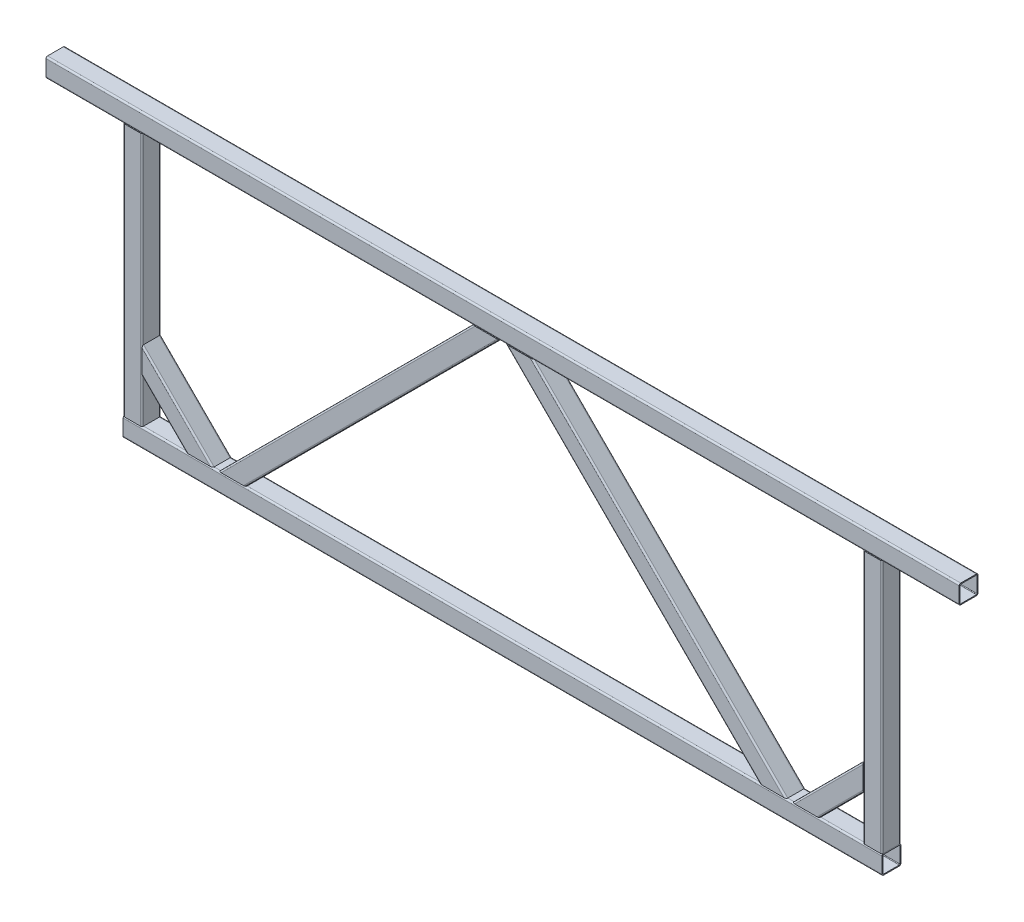
SolidWorks part; units mm, degrees
other "Вид с разнесенными частями1" [suppressed]
other "Шаг разнесения детали1" [suppressed]
other "Линия разнесения1"
other "Линия разнесения2"
other "Линия разнесения3"
other "Линия разнесения4"
other "Линия разнесения5"
other "Линия разнесения6"
other "Линия разнесения7"
other "Линия разнесения8"
other "Вид с разнесенными частями2" [suppressed]
other "3DРазнести1" [suppressed]
other "Шаг разнесения детали1" [suppressed]
other "Линия разнесения1"
ref_plane "Спереди" through (0, 0, 0) normal (0, 0, 1) x (1, 0, 0)
ref_plane "Сверху" through (0, 0, 0) normal (0, 1, 0) x (1, 0, 0)
ref_plane "Справа" through (0, 0, 0) normal (1, 0, 0) x (0, 0, -1)
sketch "Эскиз1" plane through (0, 0, 0) normal (0, 0, 1) x (1, 0, 0)
  line L0 (0, 511.5706) -> (0, -433) construction
  line L1 (-1175, 433) -> (1175, 433)
  line L2 (-1175, 433) -> (-1175, -433)
  line L3 (-1175, -433) -> (1175, -433)
  line L4 (1175, 433) -> (1175, -433)
  line L5 (-1175, 433) -> (1175, -433) construction
  line L6 (-1175, -433) -> (1175, 433) construction
  line L8 (-888.425, -433) -> (-22.425, 433)
  line L9 (-1175, -433) -> (-888.425, -433) construction
  line L10 (-888.425, -433) -> (-888.425, -84.7308) construction
  line L11 (-933.275, -433) -> (-1175, -191.275)
  line L12 (933.275, -433) -> (1175, -191.275)
  line L13 (888.425, -433) -> (22.425, 433)
  line L14 (-1450, 433) -> (1450, 433)
  point P0 (0, 0)
  dimension "D1" = 866
  dimension "D2" = 2350
  dimension "D3" = 22.425
  dimension "D4" = 44.85
  dimension "D5" = 45
  dimension "D6" = 90
  dimension "D7" = 2900
other "Прямоугольная труба 60 X 40 X 3.2(1)"
ref_plane "Плоскость1" through (-1450, 433, 0) normal (1, 0, 0) x (0, 1, 0)
sketch "Sketch1" plane through (-1450, 433, 0) normal (1, 0, 0) x (0, 1, 0)
  line L0 (-25, -27) -> (25, -27)
  line L1 (-27, -25) -> (-27, 25)
  line L2 (25, 27) -> (-25, 27)
  line L3 (27, 25) -> (27, -25)
  line L4 (-25, -30) -> (25, -30)
  line L5 (-30, -25) -> (-30, 25)
  line L6 (25, 30) -> (-25, 30)
  line L7 (30, 25) -> (30, -25)
  arc A0 (30, 25) -> (25, 30) centre (25, 25) ccw
  arc A1 (25, -30) -> (30, -25) centre (25, -25) ccw
  arc A2 (-30, -25) -> (-25, -30) centre (-25, -25) ccw
  arc A3 (-25, 30) -> (-30, 25) centre (-25, 25) ccw
  arc A4 (-25, 27) -> (-27, 25) centre (-25, 25) ccw
  arc A5 (27, 25) -> (25, 27) centre (25, 25) ccw
  arc A6 (25, -27) -> (27, -25) centre (25, -25) ccw
  arc A7 (-27, -25) -> (-25, -27) centre (-25, -25) ccw
  point P0 (0, 30)
  point P1 (30, 0)
  point P2 (0, -30)
  point P3 (-30, 0)
  point P4 (-30, 30)
  point P5 (30, 30)
  point P6 (30, -30)
  point P7 (-30, -30)
  point P8 (0, 0)
  point P33 (0, 0)
  dimension "D1" = 5
  dimension "Thickness" = 3
  dimension "V_leg" = 60
  dimension "H_leg" = 60
move or copy body "Тело-Переместить/Копировать9" [suppressed] bodies to move or copy 112 copy no translate (0, 0, 10)
move or copy body "Тело-Переместить/Копировать1" [suppressed] bodies to move or copy 115 copy no translate (0, 0, 10)
move or copy body "Тело-Переместить/Копировать2" [suppressed] bodies to move or copy 112 copy no translate (0, 0, 10)
move or copy body "Тело-Переместить/Копировать3" [suppressed] bodies to move or copy 116 copy no translate (0, 0, 10)
move or copy body "Тело-Переместить/Копировать4" [suppressed] bodies to move or copy 113 copy no translate (0, 0, 10)
move or copy body "Тело-Переместить/Копировать5" [suppressed] bodies to move or copy 119 copy no translate (0, 0, 10)
move or copy body "Тело-Переместить/Копировать6" [suppressed] bodies to move or copy 117 copy no translate (0, 0, 10)
move or copy body "Тело-Переместить/Копировать7" [suppressed] bodies to move or copy 118 copy no translate (0, 0, 10)
move or copy body "Тело-Переместить/Копировать8" [suppressed] bodies to move or copy 114 copy no translate (0, 0, 10)
